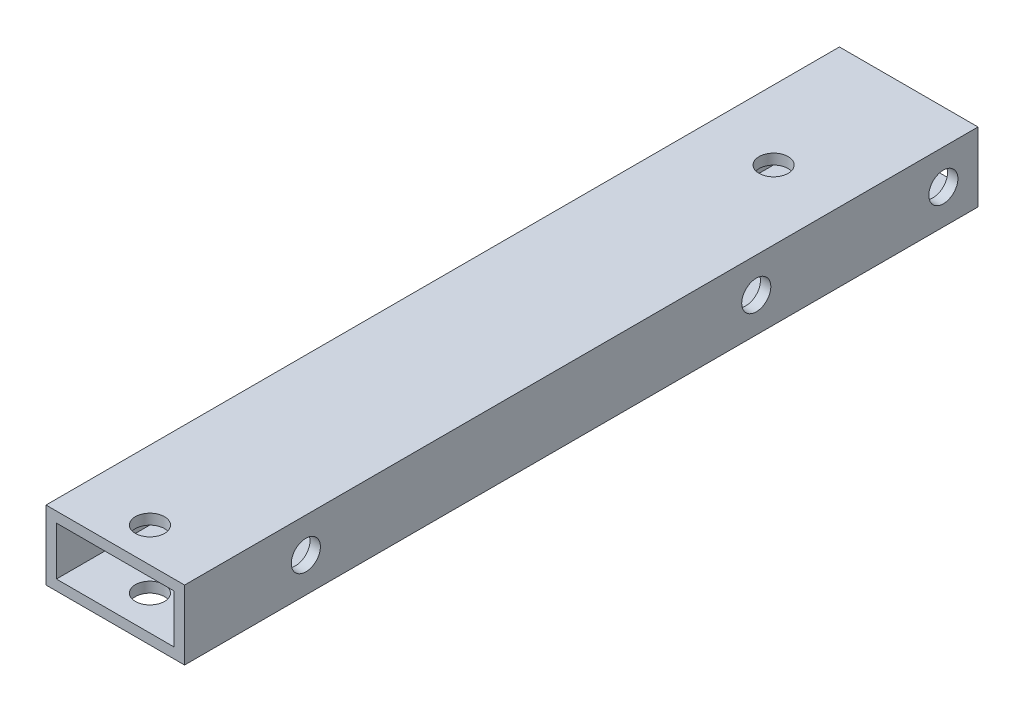
SolidWorks part; units mm, degrees
material "5052-H34"
ref_plane "正面" through (0, 0, 0) normal (0, 0, 1) x (1, 0, 0)
ref_plane "平面" through (0, 0, 0) normal (0, 1, 0) x (1, 0, 0)
ref_plane "右側面" through (0, 0, 0) normal (1, 0, 0) x (0, 0, -1)
sketch "ｽｹｯﾁ1" plane through (0, 0, 0) normal (0, 0, 1) x (1, 0, 0)
  line L1 (-10, 5) -> (10, 5)
  line L2 (-10, 5) -> (-10, -5)
  line L3 (-10, -5) -> (10, -5)
  line L4 (10, 5) -> (10, -5)
  line L5 (-10, 5) -> (10, -5) construction
  line L6 (-10, -5) -> (10, 5) construction
  point P0 (0, 0)
  dimension "D1" = 20
  dimension "D2" = 10
extrude "押し出し-薄板1" add sketch "ｽｹｯﾁ1" along normal blind 114.5 thin
sketch "ｽｹｯﾁ2" plane through (10, 0, 0) normal (1, 0, 0) x (0, 0, -1)
  line L0 (-57.25, 5) -> (-57.25, -5) construction
  line L1 (-114.5, 5) -> (0, 5) construction
  line L2 (-114.5, -5) -> (0, -5) construction
  line L3 (-64.5, 5) -> (-64.5, -5) construction
  line L4 (-64.5, 0) -> (-97, 0) construction
  line L5 (-114.5, -5) -> (-114.5, 5) construction
  circle A0 centre (-97, 0) radius 2.1
  circle A1 centre (-32, 0) radius 2.1
  dimension "D2" = 4.2
  dimension "D1" = 17.5
  dimension "D3" = 65
extrude "ｶｯﾄ - 押し出し1" cut sketch "ｽｹｯﾁ2" against normal through all
sketch "ｽｹｯﾁ3" plane through (10, 0, 0) normal (1, 0, 0) x (0, 0, -1)
  line L0 (0, 0) -> (-5, 0) construction
  circle A0 centre (-5, 0) radius 2.1
  dimension "D1" = 4.2
  dimension "D2" = 5
extrude "ｶｯﾄ - 押し出し2" cut sketch "ｽｹｯﾁ3" against normal through all
sketch "ｽｹｯﾁ4" plane through (0, 5, 0) normal (0, 1, 0) x (1, 0, 0)
  line L0 (0, -114.5) -> (0, -19.5) construction
  line L1 (10, -114.5) -> (-10, -114.5) construction
  circle A0 centre (0, -19.5) radius 2.1
  circle A1 centre (0, -109.5) radius 2.1
  dimension "D2" = 4.2
  dimension "D1" = 95
  dimension "D3" = 5
extrude "ｶｯﾄ - 押し出し3" cut sketch "ｽｹｯﾁ4" against normal through all
